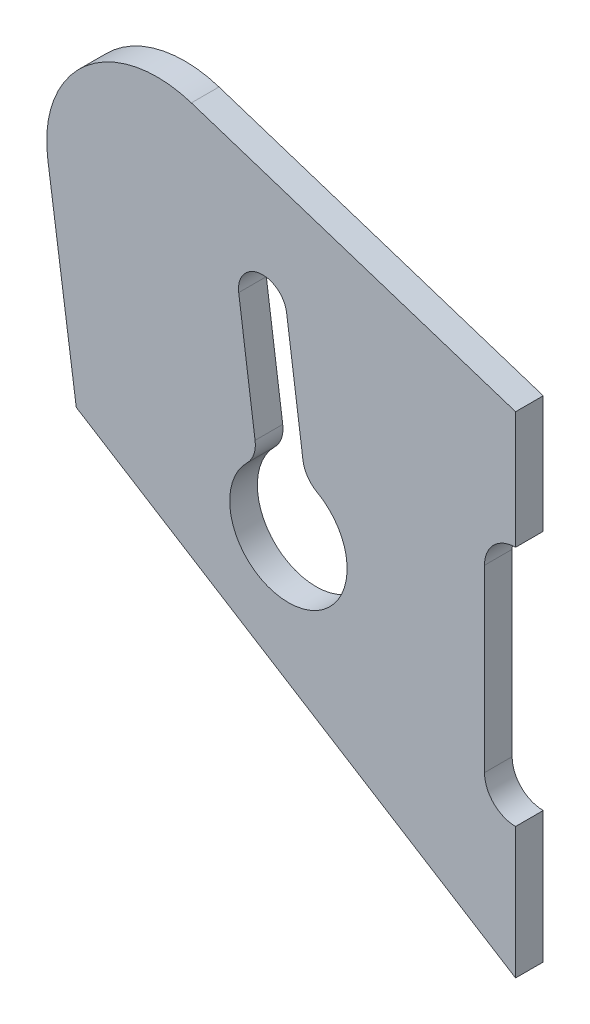
SolidWorks part; units mm, degrees
ref_plane "Front Plane" through (0, 0, 0) normal (1, 0, 0) x (0, 1, 0)
ref_plane "Top Plane" through (0, 0, 0) normal (0, 0, 1) x (0, 1, 0)
ref_plane "Right Plane" through (0, 0, 0) normal (0, 1, 0) x (-1, 0, 0)
sketch "Sketch3" plane through (0, 0, 0) normal (0, 0, 1) x (0, 1, 0)
  line L0 (0, 0) -> (38, 0)
  line L1 (0, 0) -> (79.4879, 127.2072)
  line L2 (142, 0) -> (108, 0)
  line L3 (47, 9) -> (99, 9)
  line L4 (79.4879, 127.2072) -> (137.573, 135.4513)
  line L5 (37.6243, 60.2114) -> (167.3394, 77.9866) construction
  line L6 (142, 0) -> (172.5036, 93.8803)
  line L7 (133.6858, 66.3096) -> (99.0098, 61.5578)
  line L8 (131.7851, 80.1799) -> (97.1091, 75.4282)
  line L9 (129.4177, 97.456) -> (135.829, 50.6692) construction
  arc A0 (47, 9) -> (38, 0) centre (47, 0) ccw
  arc A1 (99, 9) -> (108, 0) centre (99, 0) cw
  arc A2 (172.5036, 93.8803) -> (137.573, 135.4513) centre (142.0698, 103.7688) ccw
  arc A3 (90.3339, 77.7297) -> (93.1035, 57.5186) centre (78.2447, 65.7777) ccw
  arc A4 (133.6858, 66.3096) -> (131.7851, 80.1799) centre (132.7354, 73.2447) ccw
  arc A5 (97.1091, 75.4282) -> (90.3339, 77.7297) centre (96.023, 83.3541) cw
  arc A6 (99.0098, 61.5578) -> (93.1035, 57.5186) centre (100.0959, 53.6319) ccw
  point P11 (47, 9)
  point P14 (99, 9)
  point P16 (188.3526, 142.6585)
  point P20 (0.0968, 99.7952)
  point P29 (133.6858, 66.3096)
  point P30 (133.6858, 66.3096)
  point P31 (131.7851, 80.1799)
  dimension "D1" = 9
  dimension "D3" = 9
  dimension "D10" = 32
  dimension "D13" = 17
  dimension "D15" = 14
  dimension "D17" = 8
  dimension "D18" = 8
  dimension "D23" = 34
  dimension "D2" = 150
  dimension "D4" = 52
  dimension "D5" = 47
  dimension "D6" = 142
  dimension "D7" = 9
  dimension "D8" = 9
  dimension "D9" = 150
  dimension "D11" = 71
  dimension "D12" = 82
  dimension "D14" = 41
  dimension "D16" = 55
  dimension "D19" = 35
  dimension "D20" = 35
  dimension "D21" = 58
  dimension "D22" = 108
extrude "Boss-Extrude1" add sketch "Sketch3" along normal blind 8 contours L6 A2 L4 L1 L0 A0 L3 A1 L2 L7 A6 A3 A5 L8 A4
